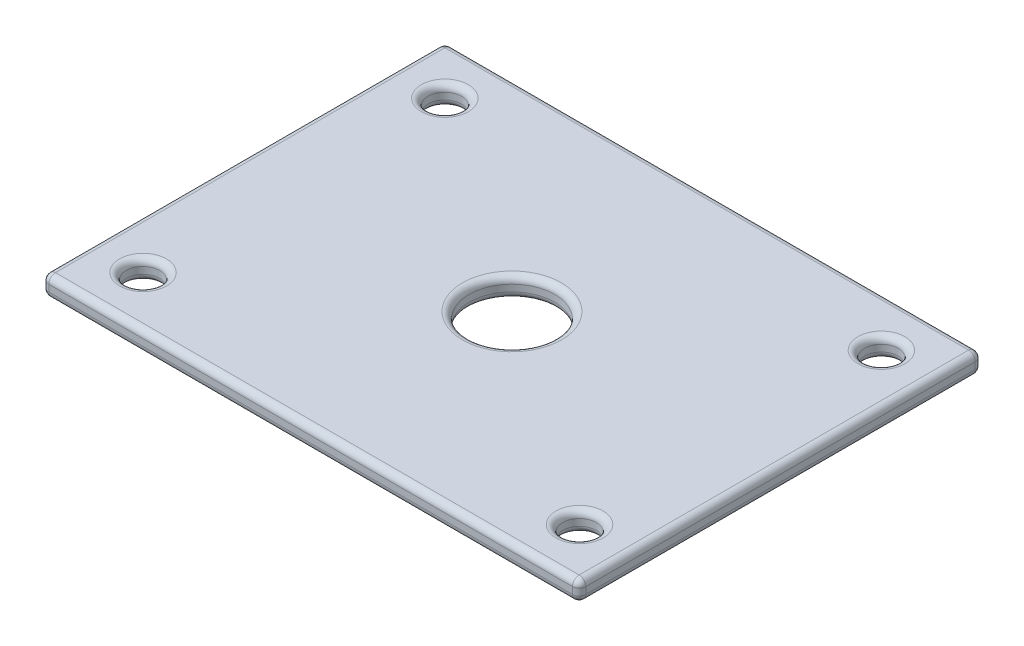
SolidWorks part; units mm, degrees
ref_plane "Front Plane" through (0, 0, 0) normal (0, 0, 1) x (1, 0, 0)
ref_plane "Top Plane" through (0, 0, 0) normal (0, 1, 0) x (1, 0, 0)
ref_plane "Right Plane" through (0, 0, 0) normal (1, 0, 0) x (0, 0, -1)
sketch "Sketch1" plane through (0, 0, 0) normal (0, 1, 0) x (1, 0, 0)
  line L1 (-51.7353, 16.3265) -> (108.2647, 16.3265)
  line L2 (-51.7353, 16.3265) -> (-51.7353, -103.6735)
  line L3 (-51.7353, -103.6735) -> (108.2647, -103.6735)
  line L4 (108.2647, 16.3265) -> (108.2647, -103.6735)
  dimension "D1" = 160
  dimension "D2" = 120
extrude "Boss-Extrude1" add sketch "Sketch1" along normal blind 6
sketch "Sketch2" plane through (0, 6, 0) normal (0, 1, 0) x (1, 0, 0)
  line L0 (-51.7353, 16.3265) -> (-51.7353, -103.6735) construction
  line L1 (108.2647, 16.3265) -> (-51.7353, 16.3265) construction
  circle A0 centre (-36.7353, 1.3265) radius 5
  circle A1 centre (93.3127, 1.3265) radius 5
  circle A2 centre (93.3127, -88.5895) radius 5
  circle A3 centre (-36.7353, -88.5895) radius 5
  circle A4 centre (28.2647, -43.6735) radius 12.75
  dimension "D2" = 10
  dimension "D6" = 25.5
  dimension "D1" = 15
  dimension "D3" = 15
  dimension "D4" = 2
  dimension "D5" = 2
extrude "Cut-Extrude1" cut sketch "Sketch2" against normal through all
fillet "Fillet1" radius 2 22 edges at (28.2647, 0, 103.6735) (108.2647, 0, 43.6735) (28.2647, 0, -16.3265) (-51.7353, 0, 43.6735) (-36.7353, 0, 3.6735) (93.3127, 0, 3.6735) (93.3127, 0, 93.5895) (-36.7353, 0, 93.5895) (28.2647, 6, -16.3265) (108.2647, 6, 43.6735) (28.2647, 6, 103.6735) (-51.7353, 6, 43.6735) (-36.7353, 6, 3.6735) (93.3127, 6, 3.6735) (93.3127, 6, 93.5895) (-36.7353, 6, 93.5895) (-51.7353, 3, -16.3265) (-51.7353, 3, 103.6735) (108.2647, 3, 103.6735) (108.2647, 3, -16.3265) (28.2647, 0, 56.4235) (28.2647, 6, 56.4235)
scale "缩放比例1" scale about origin uniform scaling yes scale factor 0.5
